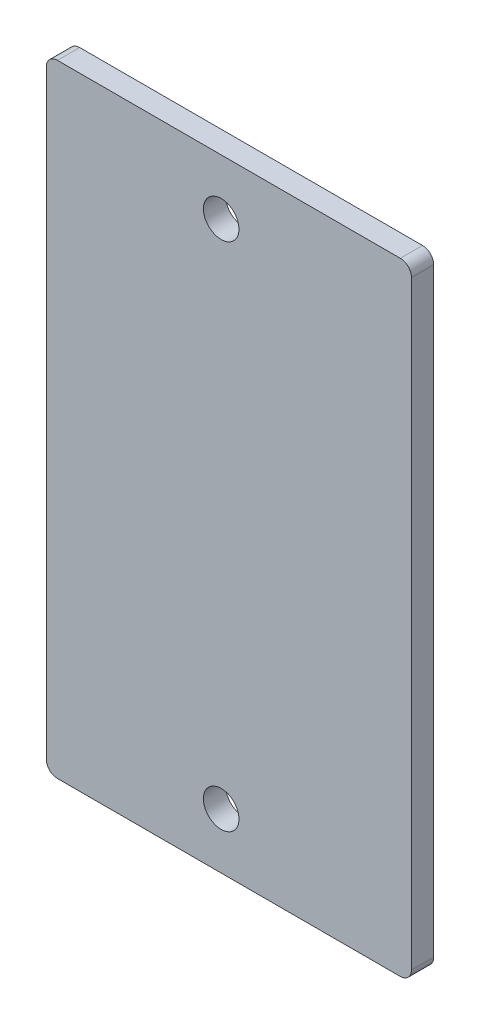
SolidWorks part; units mm, degrees
material "Thornel Mat VMA"
ref_plane "前视基准面" through (0, 0, 0) normal (0, 0, 1) x (1, 0, 0)
ref_plane "上视基准面" through (0, 0, 0) normal (0, 1, 0) x (1, 0, 0)
ref_plane "右视基准面" through (0, 0, 0) normal (1, 0, 0) x (0, 0, -1)
sketch "草图1" plane through (0, 0, 0) normal (0, 0, 1) x (1, 0, 0)
  line L0 (-65.2064, -56) -> (-34.3331, -56)
  line L3 (-33.3331, -55) -> (-33.3331, -1)
  line L5 (-33.3331, 0) -> (-66.2064, 0) construction
  line L6 (-66.2064, -55) -> (-66.2064, -1)
  line L7 (-65.2064, 0) -> (-34.3331, 0)
  circle A0 centre (-50.4651, -5) radius 1.6
  circle A1 centre (-50.4651, -51) radius 1.6
  arc A2 (-65.2064, -56) -> (-66.2064, -55) centre (-65.2064, -55) cw
  arc A3 (-34.3331, -56) -> (-33.3331, -55) centre (-34.3331, -55) ccw
  arc A4 (-33.3331, -1) -> (-34.3331, 0) centre (-34.3331, -1) ccw
  arc A5 (-66.2064, -1) -> (-65.2064, 0) centre (-65.2064, -1) cw
  point P17 (-66.2064, -56)
  point P20 (-33.3331, -56)
  point P23 (-33.3331, 0)
  point P26 (-66.2064, 0)
  dimension "D1" = 3.2
  dimension "D2" = 3.2
  dimension "D3" = 1
extrude "凸台-拉伸1" add sketch "草图1" along normal blind 2
